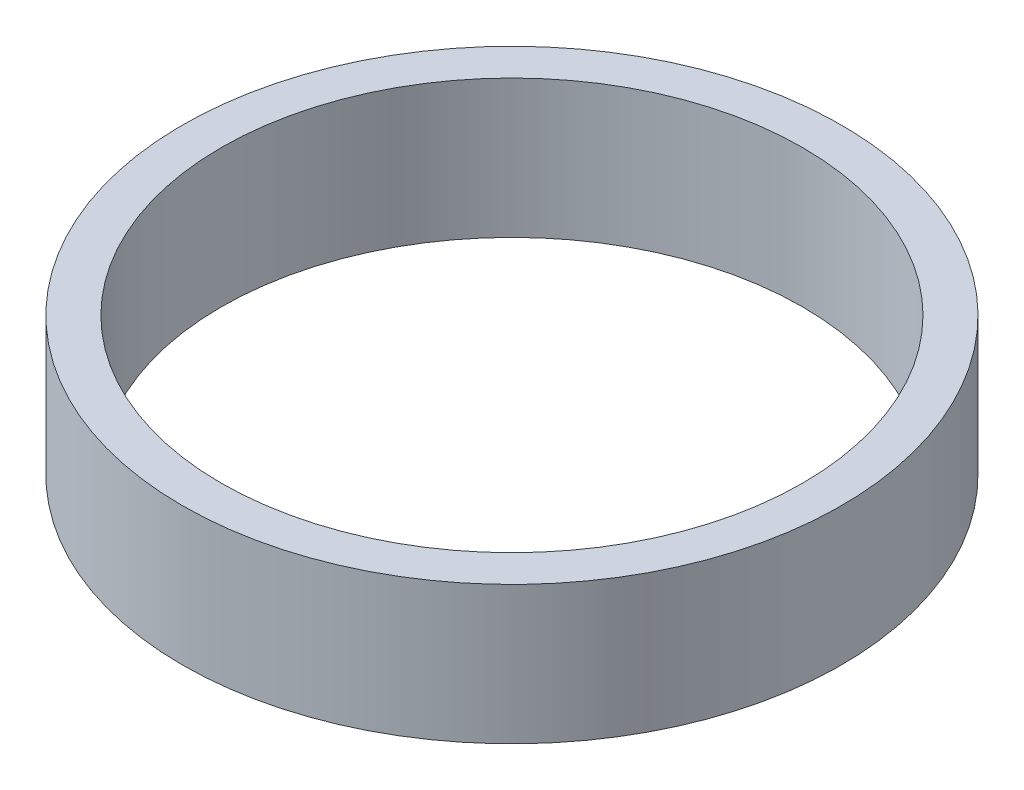
SolidWorks part; units mm, degrees
ref_plane "Front Plane" through (0, 0, 0) normal (0, 0, 1) x (1, 0, 0)
ref_plane "Top Plane" through (0, 0, 0) normal (0, 1, 0) x (1, 0, 0)
ref_plane "Right Plane" through (0, 0, 0) normal (1, 0, 0) x (0, 0, -1)
sketch "Sketch1" plane through (0, 0, 0) normal (0, 1, 0) x (1, 0, 0)
  circle A0 centre (0, 0) radius 8.8265
  circle A1 centre (0, 0) radius 10.0076
  dimension "D1" = 17.653
  dimension "D2" = 20.0152
extrude "Boss-Extrude1" add sketch "Sketch1" along normal blind 4.191
